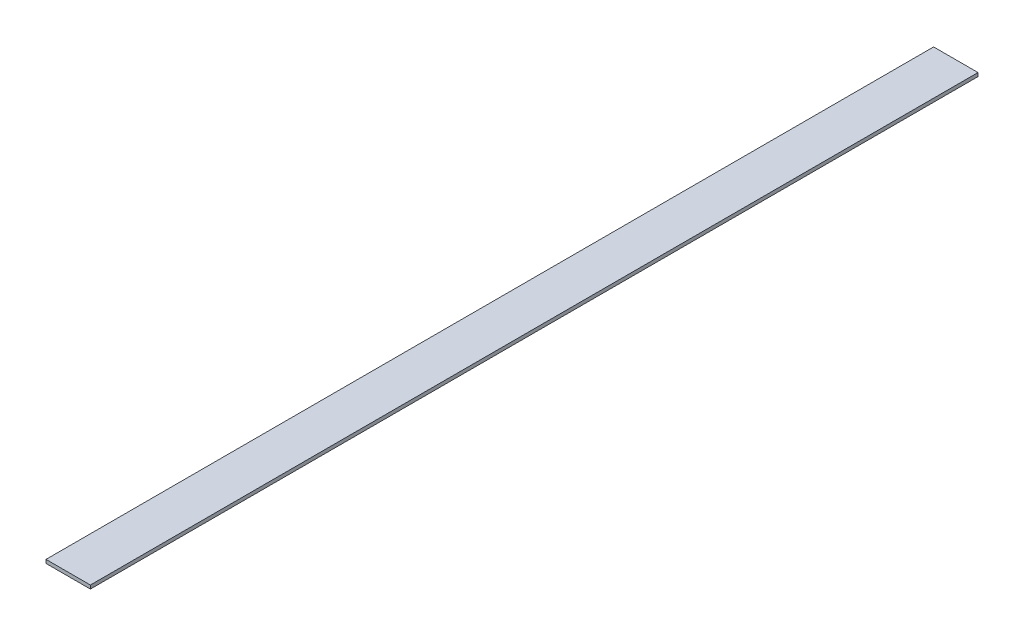
SolidWorks part; units mm, degrees
ref_plane "Front Plane" through (0, 0, 0) normal (0, 0, 1) x (1, 0, 0)
ref_plane "Top Plane" through (0, 0, 0) normal (0, 1, 0) x (1, 0, 0)
ref_plane "Right Plane" through (0, 0, 0) normal (1, 0, 0) x (0, 0, -1)
sketch "Sketch1" plane through (0, 0, 0) normal (0, 0, 1) x (1, 0, 0)
  line L1 (0, 0) -> (2, 0)
  line L2 (0, 0) -> (0, 25)
  line L3 (0, 25) -> (5, 25)
  line L4 (2, 0) -> (2, 23)
  line L5 (0, 25) -> (25, 25)
  line L6 (0, 25) -> (0, 35)
  line L7 (2, 23) -> (25, 23)
  line L8 (25, 25) -> (25, 23)
  dimension "D1" = 25
  dimension "D2" = 25
  dimension "D3" = 2
  dimension "D4" = 2
extrude "Boss-Extrude1" add sketch "Sketch1" along normal blind 500 contours L8 L5 L3 L2 L1 L4 L7
sketch "Sketch2" plane through (0, 0, 0) normal (-1, 0, 0) x (0, 0, 1)
  line L0 (500, 25) -> (0, 25) construction
  line L1 (500, 0) -> (500, 25) construction
  circle A0 centre (100, 12.5) radius 2
  circle A1 centre (200, 12.5) radius 2
  circle A2 centre (300, 12.5) radius 2
  circle A3 centre (400, 12.5) radius 2
  dimension "D1" = 12.5
  dimension "D2" = 12.5
  dimension "D3" = 12.5
  dimension "D4" = 12.5
  dimension "D5" = 100
  dimension "D6" = 100
  dimension "D7" = 100
  dimension "D8" = 100
extrude "Cut-Extrude1" cut sketch "Sketch2" against normal blind 10
sketch "Sketch3" plane through (0, 0, 0) normal (-1, 0, 0) x (0, 0, 1)
  line L0 (23, 0) -> (0, 23)
  line L1 (0, 0) -> (23, 0)
  line L2 (0, 0) -> (0, 23)
  line L5 (500, 23) -> (477, 0)
  line L6 (500, 0) -> (477, 0)
  line L7 (500, 0) -> (500, 23)
  dimension "D1" = 23
  dimension "D2" = 23
extrude "Cut-Extrude2" cut sketch "Sketch3" against normal blind 10
